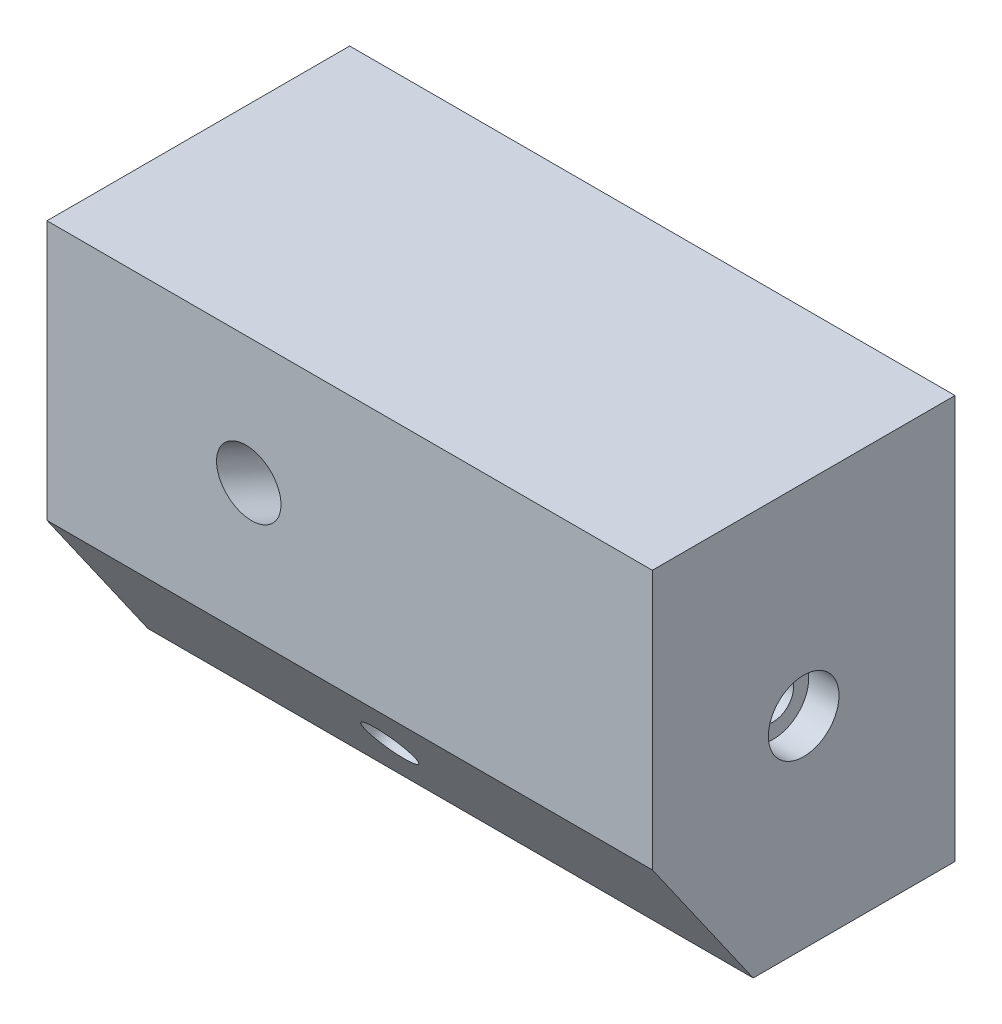
SolidWorks part; units mm, degrees
ref_plane "前视基准面" through (0, 0, 0) normal (0, 0, 1) x (1, 0, 0)
ref_plane "上视基准面" through (0, 0, 0) normal (0, 1, 0) x (1, 0, 0)
ref_plane "右视基准面" through (0, 0, 0) normal (1, 0, 0) x (0, 0, -1)
sketch "草图1" plane through (0, 0, 0) normal (0, 0, 1) x (1, 0, 0)
  line L0 (0, 0) -> (120, 0)
  line L1 (120, 0) -> (120, 80)
  line L2 (120, 80) -> (0, 80)
  line L3 (0, 80) -> (0, 0)
extrude "凸台-拉伸1" add sketch "草图1" along normal blind 60
sketch "草图2" plane through (0, 0, 0) normal (1, 0, 0) x (0, 0, -1)
  line L0 (-40, 0) -> (-62, 0)
  line L1 (-62, 0) -> (-62, 31.4192)
  line L2 (-62, 31.4192) -> (-40, 0)
extrude "切除-拉伸1" cut sketch "草图2" along normal through all
sketch3d "3D草图1"
  line L0 (36.6833, 57.4417, 69.1125) -> (58.9264, 41.0666, 8)
sweep "切除-扫描2" cut path "3D草图1" circular profile diameter 12 parameters "D3"=12
sketch "草图4" plane through (0.7386, -0.5437, -2.0292) normal (-0.3317, 0.2442, 0.9113) x (0.9434, 0.0858, 0.3204)
  arc A0 (61.6792, 31.5968) -> (61.6792, 43.5968) centre (61.6792, 37.5968) cw
  arc A1 (61.6792, 43.5968) -> (61.6792, 31.5968) centre (61.6792, 37.5968) cw
extrude "切除-拉伸2" cut sketch "草图4" against normal blind 3.6022 draft 59
sketch3d "3D草图2"
  line L0 (57.9402, 9.6929, 56.5532) -> (57.9402, 41.7926, 10.71)
sweep "切除-扫描4" cut path "3D草图2" circular profile diameter 10 parameters "D3"=10
ref_plane "基准面1" through (120, 0, 0) normal (1, 0, 0) x (0, 0, -1)
sketch "草图6" plane through (120, 0, 0) normal (1, 0, 0) x (0, 0, -1)
  circle A0 centre (-30, 40) radius 7
extrude "切除-拉伸3" cut sketch "草图6" against normal blind 6
sketch "草图7" plane through (120, 0, 0) normal (1, 0, 0) x (0, 0, -1)
  circle A0 centre (-30, 40) radius 4
extrude "切除-拉伸4" cut sketch "草图7" against normal blind 50
